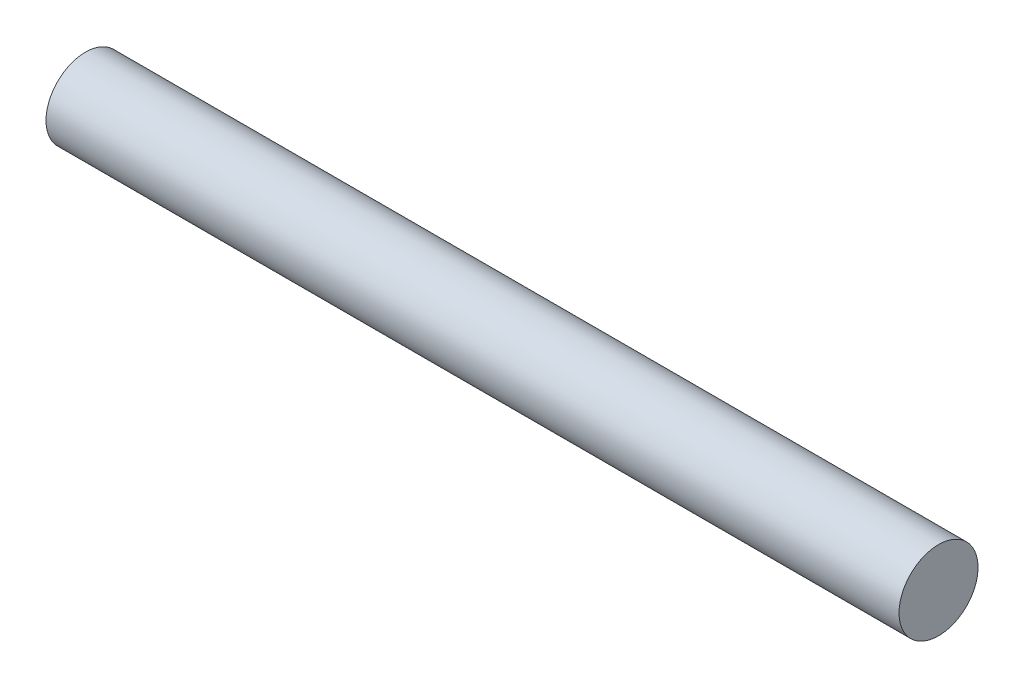
SolidWorks part; units mm, degrees
ref_plane "Front Plane" through (0, 0, 0) normal (0, 0, 1) x (1, 0, 0)
ref_plane "Top Plane" through (0, 0, 0) normal (0, 1, 0) x (1, 0, 0)
ref_plane "Right Plane" through (0, 0, 0) normal (1, 0, 0) x (0, 0, -1)
sketch "Sketch2" plane through (0, 0, 0) normal (0, 1, 0) x (1, 0, 0)
  line L0 (-33.9878, 0) -> (55.345, 0) construction
  line L1 (23.4884, 0) -> (20, 3)
  line L2 (20, 3) -> (3.4417, 3)
  line L3 (3.4417, 3) -> (1.6974, 4.5)
  line L4 (1.6974, 4.5) -> (0, 4.5)
  line L5 (0, 4.5) -> (0, 5.25)
  line L6 (0, 5.25) -> (113.2929, 5.25)
  line L7 (113.2929, 5.25) -> (113.2929, 0)
  line L8 (113.2929, 0) -> (23.4884, 0)
  dimension "D1" = 10.5
  dimension "D2" = 9
  dimension "D3" = 6
  dimension "D4" = 20
revolve "Revolve1" add sketch "Sketch2" angle 360 about L0
